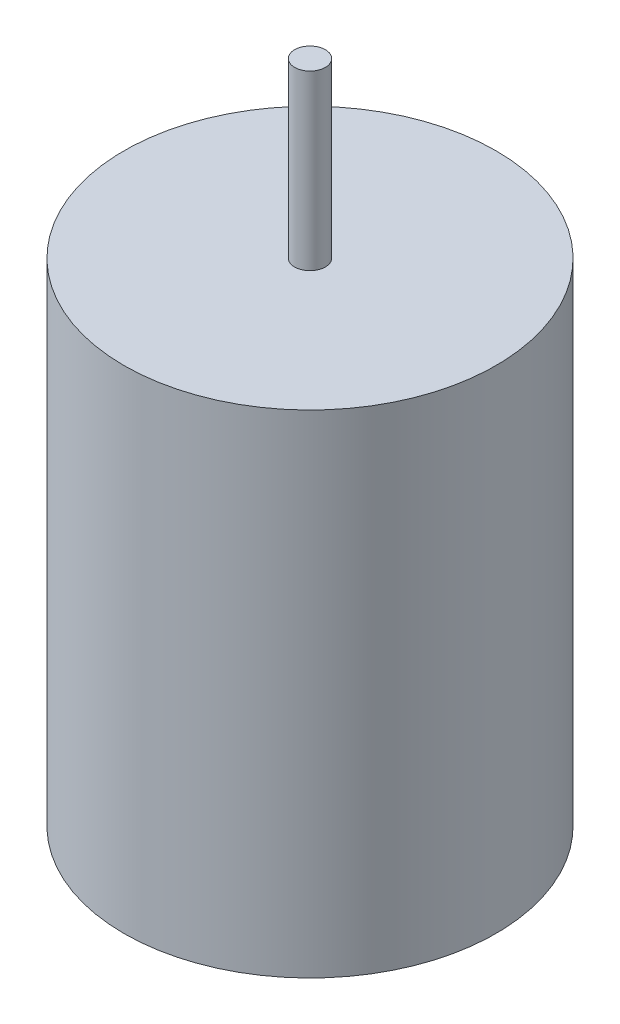
SolidWorks part; units mm, degrees
ref_plane "Front Plane" through (0, 0, 0) normal (0, 0, 1) x (1, 0, 0)
ref_plane "Top Plane" through (0, 0, 0) normal (0, 1, 0) x (1, 0, 0)
ref_plane "Right Plane" through (0, 0, 0) normal (1, 0, 0) x (0, 0, -1)
sketch "Sketch1" plane through (0, 0, 0) normal (0, 1, 0) x (1, 0, 0)
  circle A0 centre (0, 0) radius 13.9954
  dimension "D1" = 27.9908
extrude "Boss-Extrude1" add sketch "Sketch1" along normal blind 37.0078
sketch "Sketch2" plane through (0, 37.0078, 0) normal (0, 1, 0) x (1, 0, 0)
  circle A0 centre (0, 0) radius 1.1557
extrude "Boss-Extrude2" add sketch "Sketch2" along normal blind 13.0048
